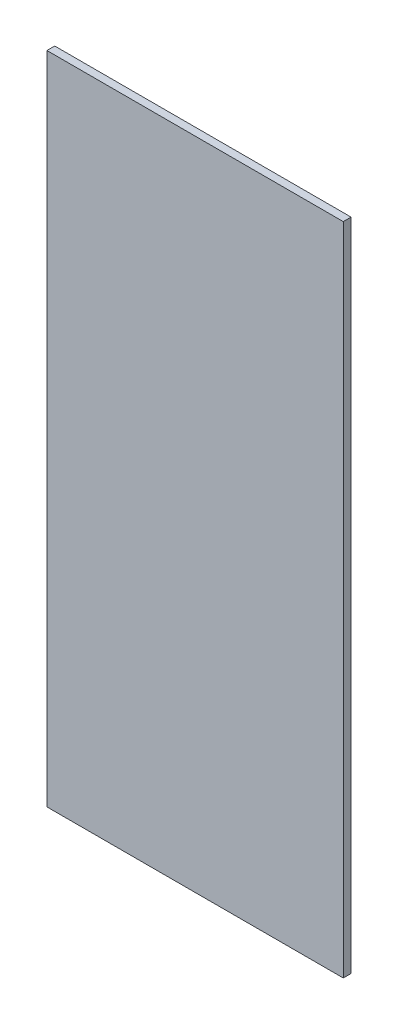
SolidWorks part; units mm, degrees
ref_plane "Plan de face" through (0, 0, 0) normal (0, 0, 1) x (1, 0, 0)
ref_plane "Plan de dessus" through (0, 0, 0) normal (0, 1, 0) x (1, 0, 0)
ref_plane "Plan de droite" through (0, 0, 0) normal (1, 0, 0) x (0, 0, -1)
sketch "Esquisse1" plane through (0, 0, 0) normal (0, 0, 1) x (1, 0, 0)
  line L1 (-95, 210) -> (95, 210)
  line L2 (-95, 210) -> (-95, -210)
  line L3 (-95, -210) -> (95, -210)
  line L4 (95, 210) -> (95, -210)
  line L5 (-95, 210) -> (95, -210) construction
  line L6 (-95, -210) -> (95, 210) construction
  point P0 (0, 0)
  dimension "D1" = 420
  dimension "D2" = 190
extrude "Boss.-Extru.1" add sketch "Esquisse1" along normal blind 5
